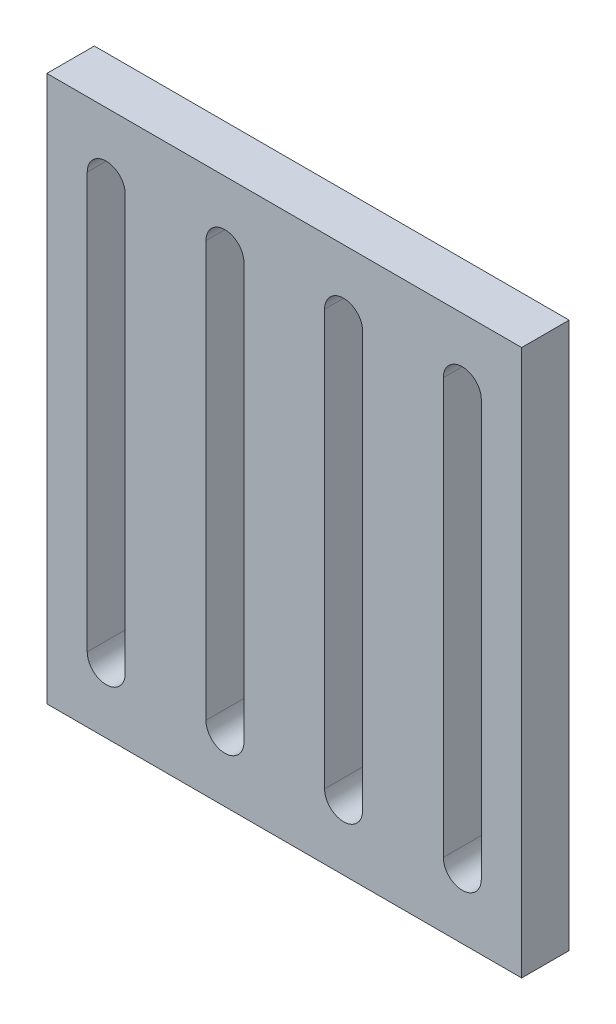
SolidWorks part; units mm, degrees
ref_plane "Front Plane" through (0, 0, 0) normal (0, 0, 1) x (1, 0, 0)
ref_plane "Top Plane" through (0, 0, 0) normal (0, 1, 0) x (1, 0, 0)
ref_plane "Right Plane" through (0, 0, 0) normal (1, 0, 0) x (0, 0, -1)
sketch "Sketch1" plane through (0, 0, 0) normal (0, 0, 1) x (1, 0, 0)
  line L0 (0, 17.5) -> (0, -17.5) construction
  line L1 (-5, -23) -> (5, -23)
  line L2 (-5, -23) -> (-5, 23)
  line L3 (-5, 23) -> (5, 23)
  line L4 (5, -23) -> (5, 23)
  line L5 (-5, -23) -> (5, 23) construction
  line L6 (-5, 23) -> (5, -23) construction
  line L7 (1.6, 17.5) -> (1.6, -17.5)
  line L8 (-1.6, 17.5) -> (-1.6, -17.5)
  arc A0 (1.6, 17.5) -> (-1.6, 17.5) centre (0, 17.5) ccw
  arc A1 (-1.6, -17.5) -> (1.6, -17.5) centre (0, -17.5) ccw
  point P0 (0, 0)
  point P8 (0, 0)
  dimension "D4" = 35
  dimension "D1" = 10
  dimension "D2" = 46
  dimension "D3" = 3.2
extrude "Boss-Extrude1" add sketch "Sketch1" along normal blind 4
pattern_linear "LPattern2" count 4 spacing 10 along (-1, 0, 0) of "Boss-Extrude1"
